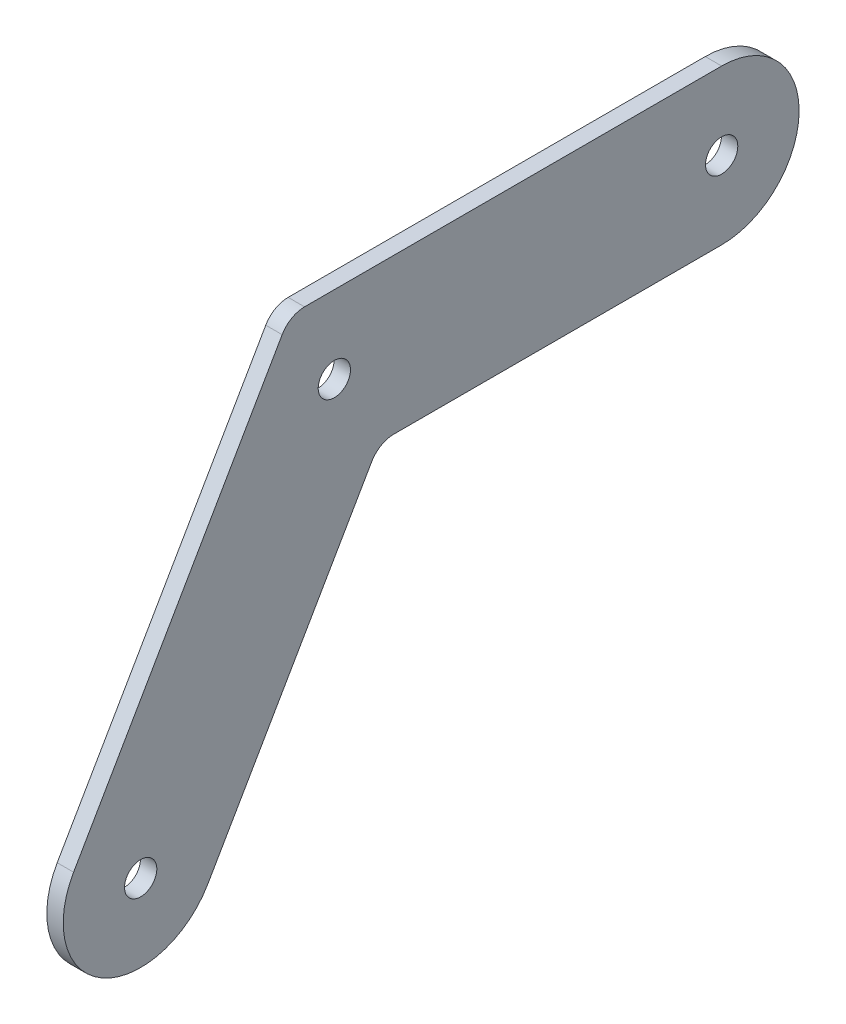
SolidWorks part; units mm, degrees
ref_plane "Alzado" through (0, 0, 0) normal (0, 0, 1) x (1, 0, 0)
ref_plane "Planta" through (0, 0, 0) normal (0, 1, 0) x (1, 0, 0)
ref_plane "Vista lateral" through (0, 0, 0) normal (1, 0, 0) x (0, 0, -1)
sketch "Croquis1" plane through (0, 0, 0) normal (1, 0, 0) x (0, 0, -1)
  line L0 (0, 0) -> (-75, -129.9038) construction
  line L1 (-17.3205, 30) -> (150, 30)
  line L2 (-17.3205, 30) -> (-100.9808, -114.9038)
  line L3 (0, 0) -> (150, 0) construction
  line L4 (17.3205, -30) -> (150, -30)
  line L5 (17.3205, -30) -> (-49.0192, -144.9038)
  arc A0 (150, 30) -> (150, -30) centre (150, 0) cw
  arc A1 (-100.9808, -114.9038) -> (-49.0192, -144.9038) centre (-75, -129.9038) ccw
  dimension "D1" = 120
  dimension "D2" = 150
  dimension "D3" = 30
  dimension "D4" = 30
extrude "Saliente-Extruir1" add sketch "Croquis1" along normal mid plane 6.35
hole_wizard "Diámetro de taladro Ø6.0 (12.5)1" positions "Croquis3" profile "Croquis4" hole size "Ø6.0" standard "Ansi Metric" end condition up to next
sketch "Croquis3" plane through (3.175, 0, 0) normal (1, 0, 0) x (0, 0, -1)
  arc A0 (-100.9808, -114.9038) -> (-49.0192, -144.9038) centre (-75, -129.9038) ccw construction
  arc A1 (150, -30) -> (150, 30) centre (150, 0) ccw construction
  point P0 (0, 0)
  point P3 (-75, -129.9038)
  point P5 (150, 0)
sketch "Croquis4" plane through (3.175, 0, 0) normal (0, 1, 0) x (0, 0, -1)
  line L0 (0, 0) -> (0, 6.35)
  line L1 (0, 6.35) -> (6.25, 6.35)
  line L2 (6.25, 6.35) -> (6.25, 0)
  line L5 (6.25, 0) -> (0, 0)
  line L11 (0, -6.35) -> (0, 107.95) construction
  dimension "Diámetro de taladro hasta el siguiente" = 12.5
  dimension "Profundidad de taladro hasta el siguiente" = 6.35
fillet "Redondeo1" radius 10 2 edges at (0, -30, -17.3205) (0, 30, 17.3205)
